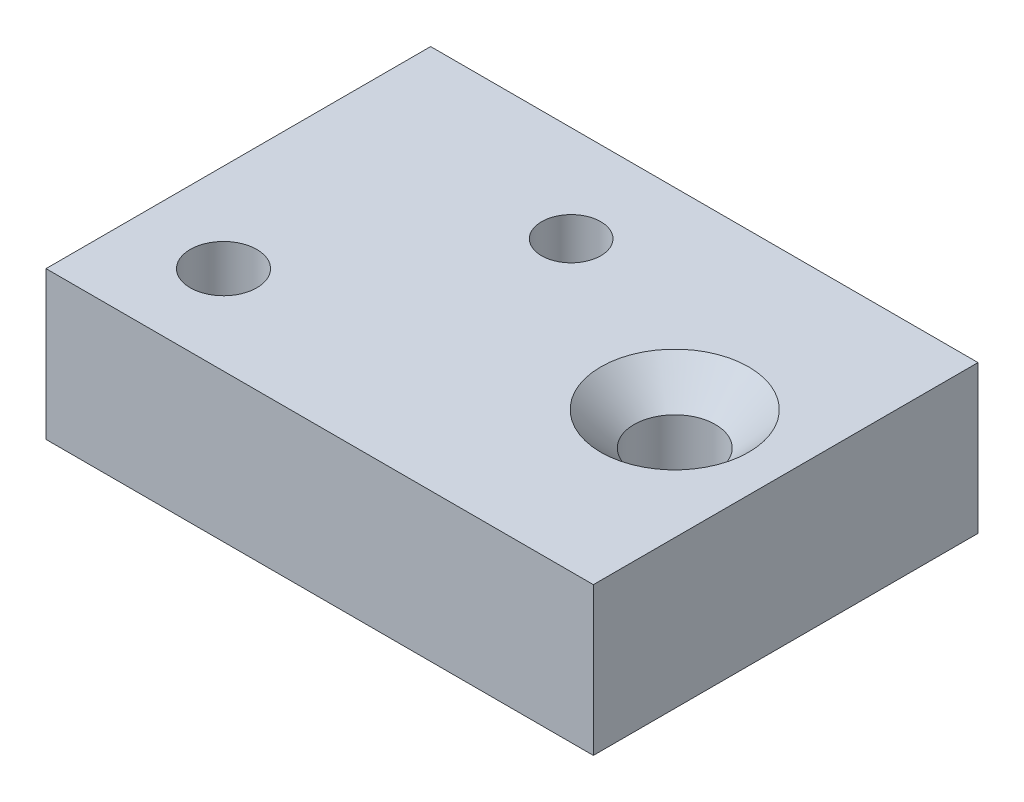
SolidWorks part; units mm, degrees
ref_plane "Front Plane" through (0, 0, 0) normal (0, 0, 1) x (1, 0, 0)
ref_plane "Top Plane" through (0, 0, 0) normal (0, 1, 0) x (1, 0, 0)
ref_plane "Right Plane" through (0, 0, 0) normal (1, 0, 0) x (0, 0, -1)
sketch "Sketch1" plane through (0, 0, 0) normal (0, 1, 0) x (1, 0, 0)
  line L0 (-32, -26) -> (42, -26)
  line L1 (-32, 0) -> (42, 0) construction
  line L2 (-32, -26) -> (-32, 26)
  line L3 (-32, 26) -> (42, 26)
  line L4 (42, -26) -> (42, 26)
  dimension "D1" = 74
  dimension "D2" = 52
  dimension "D3" = 32
extrude "Extrude1" add sketch "Sketch1" along normal blind 20
hole_wizard "CSK for M10 Flat Head Machine Screw1" positions "Sketch3" profile "Sketch2" countersink size "M10" standard "Ansi Metric" end condition through all
sketch "Sketch3" plane through (0, 20, 0) normal (0, 1, 0) x (-1, 0, 0)
  point P0 (-27, 0)
  dimension "D1" = 27
sketch "Sketch2" plane through (27, 20, 0) normal (1, 0, 0) x (0, 0, 1)
  line L0 (0, 0) -> (0, 20)
  line L1 (0, 20) -> (5.5, 20)
  line L2 (5.5, 20) -> (5.5, 4.5)
  line L3 (5.5, 4.5) -> (10, 0)
  line L5 (10, 0) -> (0, 0)
  line L6 (-5.5, 4.5) -> (-10, 0) construction
  line L11 (0, -6.35) -> (0, 107.95) construction
  dimension "Thru Hole Dia." = 11
  dimension "Thru Hole Depth" = 20
  dimension "Near C'Sink Dia." = 20
  dimension "Near C'Sink Angle" = 90
hole_wizard "Ø8.0 (8) Diameter Hole1" positions "Sketch5" profile "Sketch4" hole size "Ø8.0" standard "BSI" end condition through all
sketch "Sketch5" plane through (0, 20, 0) normal (0, 1, 0) x (-1, 0, 0)
  point P0 (0, -13)
  dimension "D1" = 13
sketch "Sketch4" plane through (0, 20, -13) normal (1, 0, 0) x (0, 0, 1)
  line L0 (0, 0) -> (0, 20)
  line L1 (0, 20) -> (4, 20)
  line L2 (4, 20) -> (4, 0)
  line L5 (4, 0) -> (0, 0)
  line L11 (0, -6.35) -> (0, 107.95) construction
  dimension "Thru Hole Dia." = 8
  dimension "Thru Hole Depth" = 20
hole_wizard "CBORE for M8 SHCS1" positions "Sketch7" profile "Sketch6" counterbore size "M8" standard "Ansi Metric" end condition through all
sketch "Sketch7" plane through (0, 0, 0) normal (0, -1, 0) x (1, 0, 0)
  point P0 (-20, 14)
  dimension "D1" = 20
  dimension "D2" = 14
sketch "Sketch6" plane through (-20, 0, 14) normal (1, 0, 0) x (0, 0, -1)
  line L0 (0, 0) -> (0, 20)
  line L1 (0, 20) -> (4.5, 20)
  line L3 (4.5, 20) -> (4.5, 8)
  line L4 (4.5, 8) -> (7.5, 8)
  line L5 (7.5, 8) -> (7.5, 0)
  line L7 (7.5, 0) -> (0, 0)
  line L11 (0, -6.35) -> (0, 107.95) construction
  dimension "Thru Hole Dia." = 9
  dimension "Thru Hole Depth" = 20
  dimension "C'Bore Dia." = 15
  dimension "C'Bore Depth" = 8
ref_plane "Plane1" through (0, 13, 0) normal (0, 1, 0) x (-1, 0, 0)
sketch "Sketch8" plane through (0, 13, 0) normal (0, 1, 0) x (-1, 0, 0)
  circle A0 centre (0, -13) radius 8
  dimension "D1" = 16
extrude "Cut-Extrude1" cut sketch "Sketch8" against normal blind 6
